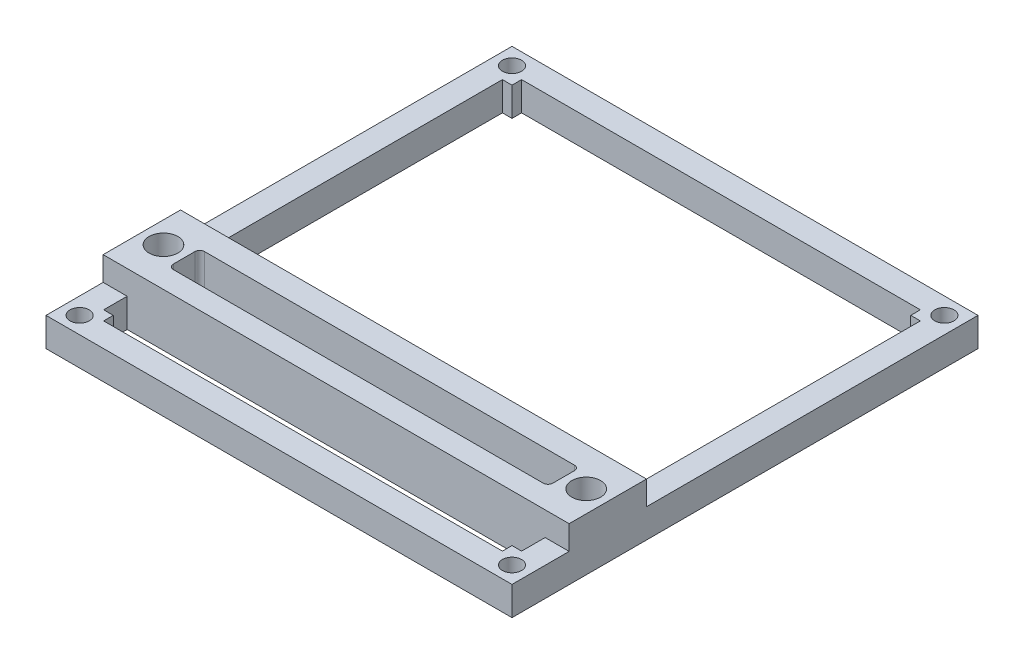
SolidWorks part; units mm, degrees
ref_plane "Front" through (0, 0, 0) normal (0, 0, 1) x (1, 0, 0)
ref_plane "Top" through (0, 0, 0) normal (0, 1, 0) x (1, 0, 0)
ref_plane "Right" through (0, 0, 0) normal (1, 0, 0) x (0, 0, -1)
sketch "Sketch1" plane through (0, 0, 0) normal (0, 1, 0) x (1, 0, 0)
  line L1 (0, 0) -> (97, 0)
  line L2 (0, 0) -> (0, 97)
  line L3 (0, 97) -> (97, 97)
  line L4 (97, 0) -> (97, 97)
  line L9 (90, 92) -> (7, 92)
  line L10 (92, 90) -> (92, 28)
  line L12 (5, 90) -> (5, 28)
  line L13 (92, 92) -> (5, 5) construction
  line L14 (92, 5) -> (5, 92) construction
  line L21 (92, 23) -> (92, 16.5)
  line L26 (7, 5) -> (90, 5)
  line L27 (5, 7) -> (5, 11.8934)
  line L28 (5, 11.8934) -> (92, 11.8934)
  line L29 (92, 7) -> (92, 11.8934)
  line L30 (92, 16.5) -> (5, 16.5)
  line L31 (92, 16.5) -> (92, 23)
  line L32 (92, 23) -> (5, 23)
  line L33 (5, 16.5) -> (5, 23)
  line L34 (5, 23) -> (92, 23)
  line L36 (5, 28) -> (92, 28)
  line L38 (97, 97) -> (90, 97)
  line L39 (97, 97) -> (97, 90)
  line L42 (0, 97) -> (7, 97)
  line L43 (0, 97) -> (0, 90)
  line L44 (5, 90) -> (7, 90)
  line L45 (7, 92) -> (7, 90)
  line L46 (0, 0) -> (7, 0)
  line L47 (0, 0) -> (0, 7)
  line L48 (0, 7) -> (7, 7)
  line L49 (7, 5) -> (7, 7)
  line L50 (97, 0) -> (90, 0)
  line L51 (97, 0) -> (97, 7)
  line L52 (92, 7) -> (90, 7)
  line L53 (90, 5) -> (90, 7)
  line L54 (97, 97) -> (90, 97)
  line L55 (97, 97) -> (97, 90)
  line L56 (92, 90) -> (90, 90)
  line L57 (90, 92) -> (90, 90)
  line L58 (5, 23) -> (5, 16.8934)
  line L59 (92, 90) -> (92, 92)
  point P5 (48.5, 0)
  point P6 (0, 48.5)
  point P7 (48.5, 48.5)
  dimension "D1" = 97
  dimension "D2" = 6.5
  dimension "D3" = 5
  dimension "D4" = 5
  dimension "D5" = 5
  dimension "D6" = 5
  dimension "D8" = 7
  dimension "D9" = 7
  dimension "D10" = 7
extrude "Boss-Extrude1" add sketch "Sketch1" along normal blind 6
sketch "Sketch6" plane through (0, 0, 0) normal (0, -1, 0) x (1, 0, 0)
  line L5 (92, -23) -> (5, -23)
  line L6 (92, -23) -> (92, -16.5)
  line L7 (92, -16.5) -> (5, -16.5)
  line L8 (5, -23) -> (5, -16.5)
extrude "Boss-Extrude2" add sketch "Sketch6" against normal blind 2
sketch "Sketch7" plane through (0, 6, 0) normal (0, 1, 0) x (1, 0, 0)
  line L0 (0, 0) -> (0, 97) construction
  line L1 (97, 0) -> (97, 97) construction
  line L2 (0, 0) -> (0, 97) construction
  line L19 (97, 28) -> (0, 28)
  line L20 (97, 28) -> (97, 11.8934)
  line L21 (97, 11.8934) -> (0, 11.8934)
  line L22 (0, 28) -> (0, 11.8934)
  line L24 (92, 23) -> (5, 23)
  line L25 (92, 23) -> (92, 16.5)
  line L26 (92, 16.5) -> (5, 16.5)
  line L27 (5, 23) -> (5, 16.5)
  point P0 (5, 28)
  point P1 (0, 28)
  point P3 (92, 28)
  point P6 (97, 28)
  point P8 (5, 11.8934)
  point P11 (92, 11.8934)
extrude "Boss-Extrude3" add sketch "Sketch7" along normal blind 5
sketch "Sketch8" plane through (0, 6, 0) normal (0, 1, 0) x (1, 0, 0)
  line L9 (97, 97) -> (90, 97)
  line L10 (97, 97) -> (97, 90)
  line L11 (97, 90) -> (90, 90)
  line L12 (90, 97) -> (90, 90)
  line L13 (7, 7) -> (0, 7)
  line L14 (7, 7) -> (7, 0)
  line L15 (7, 0) -> (0, 0)
  line L16 (0, 7) -> (0, 0)
  circle A0 centre (93.5, 93.5) radius 2
  circle A1 centre (3.5, 3.5) radius 2
  circle A2 centre (3.5, 93.5) radius 2
  circle A3 centre (93.5, 3.5) radius 2
  point P4 (7, 3.5)
  point P6 (97, 93.5)
  point P7 (93.5, 97)
  point P29 (3.5, 7)
  dimension "D1" = 4
  dimension "D2" = 4
extrude "Cut-Extrude1" cut sketch "Sketch8" against normal through all contours A0 | A3 | A1 | A2
sketch "Sketch10" plane through (0, 2, 0) normal (0, 1, 0) x (1, 0, 0)
  line L5 (92, 16.5) -> (5, 16.5) construction
  line L6 (92, 23) -> (88, 23)
  line L7 (92, 23) -> (92, 16.5)
  line L8 (92, 16.5) -> (88, 16.5)
  line L9 (88, 23) -> (88, 16.5)
  line L10 (5, 16.5) -> (92, 16.5) construction
  line L11 (5, 23) -> (9, 23)
  line L12 (5, 23) -> (5, 16.5)
  line L13 (5, 16.5) -> (9, 16.5)
  line L14 (9, 23) -> (9, 16.5)
  dimension "D1" = 4
  dimension "D2" = 4
extrude "Boss-Extrude4" add sketch "Sketch10" along normal blind 9
sketch "Sketch11" plane through (0, 11, 0) normal (0, 1, 0) x (1, 0, 0)
  line L0 (97, 11.8934) -> (97, 28) construction
  line L1 (0, 28) -> (0, 11.8934) construction
  line L2 (0, 11.8934) -> (97, 11.8934) construction
  circle A0 centre (92.5, 19.9467) radius 3
  circle A1 centre (4.5, 19.9467) radius 3
  point P0 (97, 19.9467)
  point P1 (0, 19.9467)
  point P10 (97, 11.8934)
  point P11 (88, 16.5)
  point P13 (88, 11.8934)
  dimension "D1" = 6
  dimension "D2" = 4.5
  dimension "D3" = 4.5
extrude "Cut-Extrude2" cut sketch "Sketch11" against normal blind 21
fillet "Fillet1" radius 1 4 edges at (9, 6.5, -16.5) (9, 6.5, -23) (88, 6.5, -23) (88, 6.5, -16.5)
